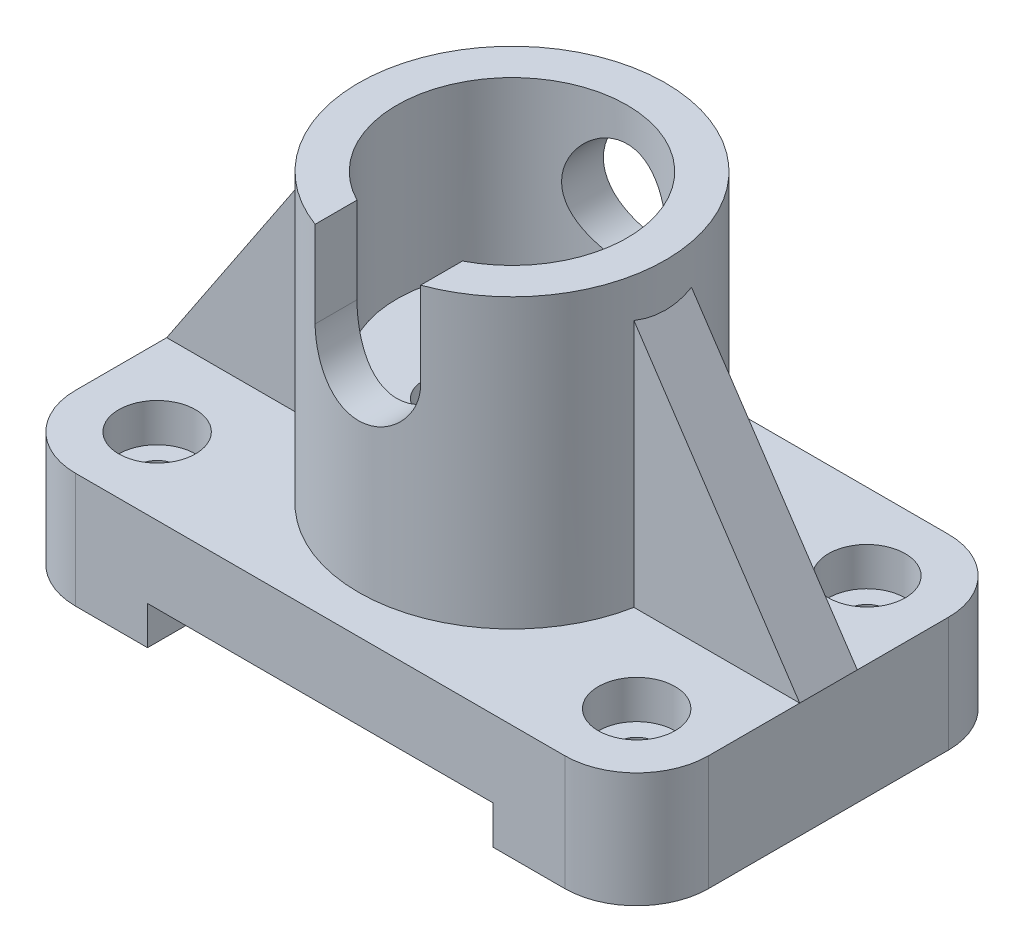
SolidWorks part; units mm, degrees
ref_plane "前视基准面" through (0, 0, 0) normal (0, 0, 1) x (1, 0, 0)
ref_plane "上视基准面" through (0, 0, 0) normal (0, 1, 0) x (1, 0, 0)
ref_plane "右视基准面" through (0, 0, 0) normal (1, 0, 0) x (0, 0, -1)
other "Configuration Table"
sketch "草图1" plane through (0, 0, 0) normal (0, 1, 0) x (1, 0, 0)
  line L1 (51, 40) -> (-51, 40)
  line L2 (66, 25) -> (66, -25)
  line L3 (51, -40) -> (-51, -40)
  line L4 (-66, 25) -> (-66, -25)
  line L5 (66, 40) -> (-66, -40) construction
  line L6 (66, -40) -> (-66, 40) construction
  circle A0 centre (-50, 24) radius 4
  circle A1 centre (50, 24) radius 4
  circle A2 centre (50, -24) radius 4
  circle A3 centre (-50, -24) radius 4
  arc A4 (51, 40) -> (66, 25) centre (51, 25) cw
  arc A5 (66, -25) -> (51, -40) centre (51, -25) cw
  arc A6 (-51, -40) -> (-66, -25) centre (-51, -25) cw
  arc A7 (-51, 40) -> (-66, 25) centre (-51, 25) ccw
  point P0 (0, 0)
  dimension "D3" = 50
  dimension "D5" = 8
  dimension "D8" = 15
  dimension "D1" = 132
  dimension "D2" = 80
  dimension "D4" = 24
  dimension "D6" = 2
  dimension "D7" = 2
extrude "凸台-拉伸1" add sketch "草图1" along normal blind 24
sketch "草图2" plane through (0, 0, 40) normal (0, 0, 1) x (1, 0, 0)
  line L1 (36, -8) -> (-36, -8)
  line L2 (36, -8) -> (36, 8)
  line L3 (36, 8) -> (-36, 8)
  line L4 (-36, -8) -> (-36, 8)
  line L5 (36, -8) -> (-36, 8) construction
  line L6 (36, 8) -> (-36, -8) construction
  point P0 (0, 0)
  dimension "D1" = 16
  dimension "D2" = 72
extrude "切除-拉伸1" cut sketch "草图2" against normal through all
sketch "草图3" plane through (0, 24, 0) normal (0, 1, 0) x (1, 0, 0)
  circle A0 centre (-50, 24) radius 8
  circle A1 centre (50, 24) radius 8
  circle A2 centre (50, -24) radius 8
  circle A3 centre (-50, -24) radius 8
  dimension "D1" = 2
  dimension "D2" = 2
extrude "切除-拉伸2" cut sketch "草图3" against normal blind 8
sketch "草图5" plane through (0, 24, 0) normal (0, 1, 0) x (1, 0, 0)
  circle A0 centre (0, 0) radius 32
extrude "凸台-拉伸2" add sketch "草图5" along normal blind 60
sketch "草图6" plane through (0, 84, 0) normal (0, 1, 0) x (1, 0, 0)
  circle A0 centre (0, 0) radius 24
extrude "切除-拉伸3" cut sketch "草图6" against normal blind 35
sketch "草图7" plane through (0, 49, 0) normal (0, 1, 0) x (1, 0, 0)
  line L1 (6.5, -12) -> (-6.5, -12)
  line L2 (-6.5, -12) -> (-6.5, 0)
  line L3 (-6.5, 0) -> (-13, 0)
  line L4 (-13, 0) -> (-13, 10)
  line L5 (-13, 10) -> (13, 10)
  line L6 (6.5, -12) -> (6.5, 0)
  line L7 (13, 0) -> (13, 10)
  line L8 (6.5, 0) -> (13, 0)
  point P11 (0, 10)
  dimension "D1" = 13
  dimension "D2" = 26
  dimension "D3" = 6.5
  dimension "D4" = 10
  dimension "D5" = 13
extrude "切除-拉伸4" cut sketch "草图7" against normal blind 15
sketch "草图8" plane through (0, 49, 0) normal (0, 1, 0) x (1, 0, 0)
  line L0 (-6.5, -12) -> (6.5, -12) construction
  circle A0 centre (0, -12) radius 6.5
extrude "切除-拉伸5" cut sketch "草图8" against normal blind 86
sketch "草图9" plane through (0, 0, 40) normal (0, 0, 1) x (1, 0, 0)
  line L0 (32, 84) -> (-32, 84) construction
  circle A0 centre (0, 66) radius 11
  dimension "D1" = 18
  dimension "D2" = 22
extrude "切除-拉伸6" cut sketch "草图9" against normal blind 86
sketch "草图10" plane through (0, 0, 40) normal (0, 0, 1) x (1, 0, 0)
  line L0 (-11, 66) -> (11, 66)
  line L1 (-11, 66) -> (-11, 87.7226)
  line L2 (11, 66) -> (11, 87.7226)
  line L3 (-11, 87.7226) -> (11, 87.7226)
  circle A0 centre (0, 66) radius 11 construction
extrude "切除-拉伸7" cut sketch "草图10" against normal blind 38
sketch "草图12" plane through (0, 0, 0) normal (0, 0, 1) x (1, 0, 0)
  line L0 (-66, 24) -> (-30.935, 76.5519)
  point P3 (-31.9705, 75)
  dimension "D1" = 51
rib "筋8" sketch "草图12" sketch "草图12" thickness 12 extrusion direction parallel to sketch draft on no parameters "D1"=12
mirror "镜向2" about plane through (0, 0, 0) normal (1, 0, 0) of "筋8"
